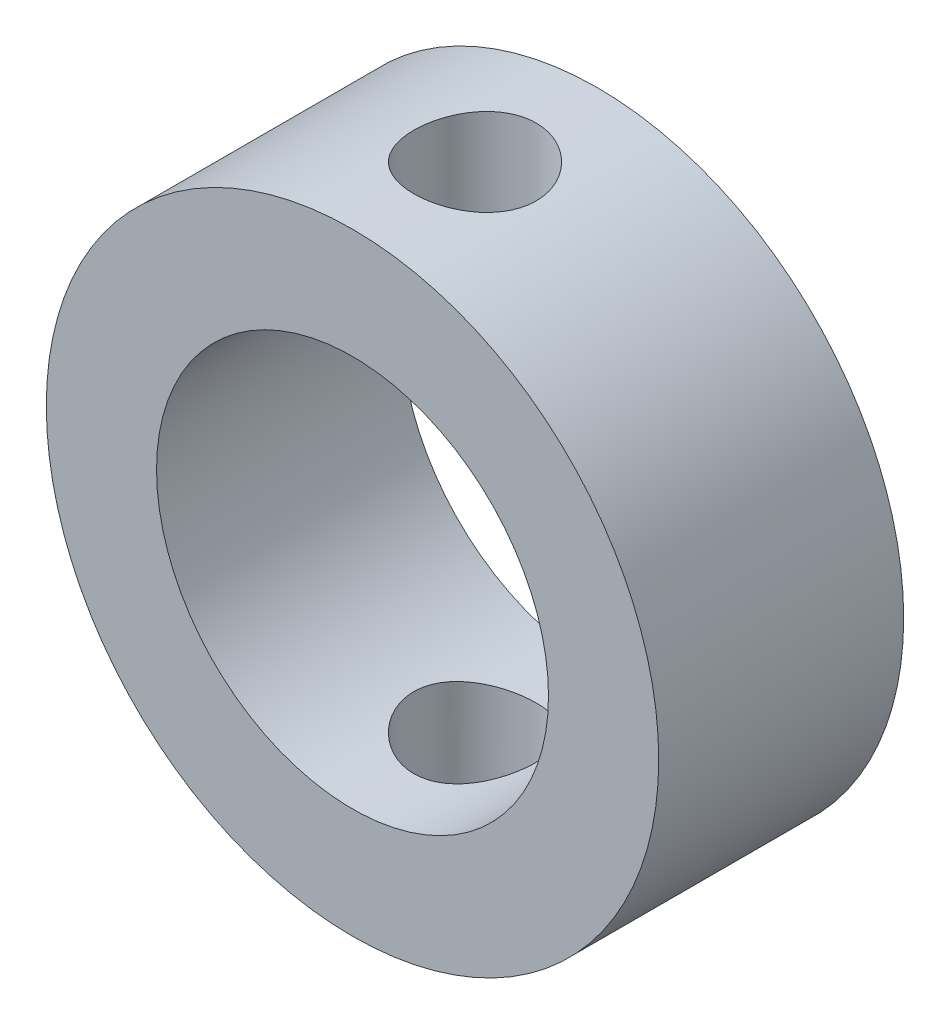
SolidWorks part; units mm, degrees
ref_plane "Front Plane" through (0, 0, 0) normal (0, 0, 1) x (1, 0, 0)
ref_plane "Top Plane" through (0, 0, 0) normal (0, 1, 0) x (1, 0, 0)
ref_plane "Right Plane" through (0, 0, 0) normal (1, 0, 0) x (0, 0, -1)
sketch "Sketch1" plane through (0, 0, 0) normal (0, 0, 1) x (1, 0, 0)
  circle A0 centre (0, 0) radius 12.5
  circle A1 centre (0, 0) radius 8
  dimension "D1" = 25
  dimension "D2" = 16
extrude "Boss-Extrude1" add sketch "Sketch1" along normal blind 10
sketch "Sketch2" plane through (0, 0, 0) normal (0, 1, 0) x (1, 0, 0)
  circle A0 centre (0, -5) radius 2.5
extrude "Cut-Extrude1" cut sketch "Sketch2" against normal mid plane 100
